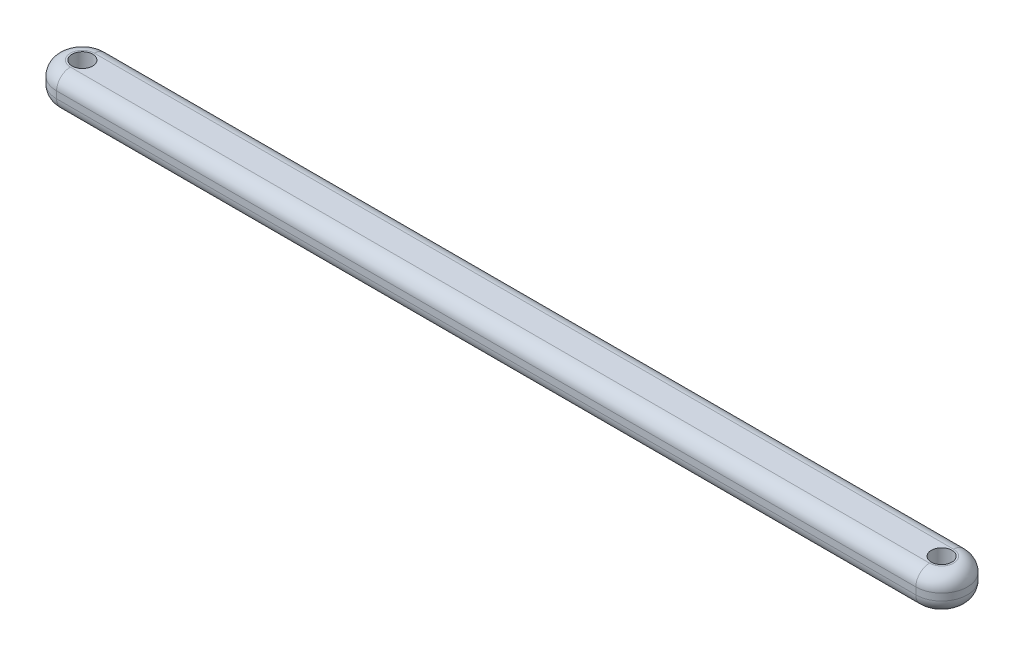
SolidWorks part; units mm, degrees
material "ABS PC"
ref_plane "Alzado" through (0, 0, 0) normal (1, 0, 0) x (0, 1, 0)
ref_plane "Planta" through (0, 0, 0) normal (0, 0, 1) x (0, 1, 0)
ref_plane "Vista lateral" through (0, 0, 0) normal (0, 1, 0) x (-1, 0, 0)
sketch "Croquis1" plane through (0, 0, 0) normal (0, 1, 0) x (-1, 0, 0)
  line L0 (0, 0) -> (250, 0) construction
  line L6 (0, -7.5) -> (250, -7.5)
  line L8 (250, 7.5) -> (0, 7.5)
  line L9 (125, -7.5) -> (125, 0) construction
  circle A0 centre (0, 0) radius 3
  circle A1 centre (250, 0) radius 3
  arc A3 (250, -7.5) -> (257.5, 0) centre (250, 0) ccw construction
  arc A9 (250, -7.5) -> (257.5, 0) centre (250, 0) ccw construction
  arc A10 (250, -7.5) -> (250, 7.5) centre (250, 0) ccw
  arc A12 (0, -7.5) -> (0, 7.5) centre (0, 0) cw
  dimension "D3" = 6
  dimension "D1" = 250
  dimension "D2" = 15
extrude "Saliente-Extruir1" add sketch "Croquis1" along normal mid plane 10
fillet "Redondeo3" radius 4 8 edges at (-257.5, 5, 0) (-257.5, -5, 0) (-125, 5, 7.5) (-125, -5, 7.5) (7.5, 5, 0) (7.5, -5, 0) (-125, 5, -7.5) (-125, -5, -7.5)
equation "\"L1\"= 250"
equation "\"ancho\"= 15"
equation "\"esp\"= 10"
equation "\"agujeros\"= 6"
equation "\"D1@Croquis1\"=\"L1\""
equation "\"D2@Croquis1\"=\"ancho\""
equation "\"D3@Croquis1\"=\"agujeros\""
equation "\"D1@Saliente-Extruir1\"=\"esp\""
